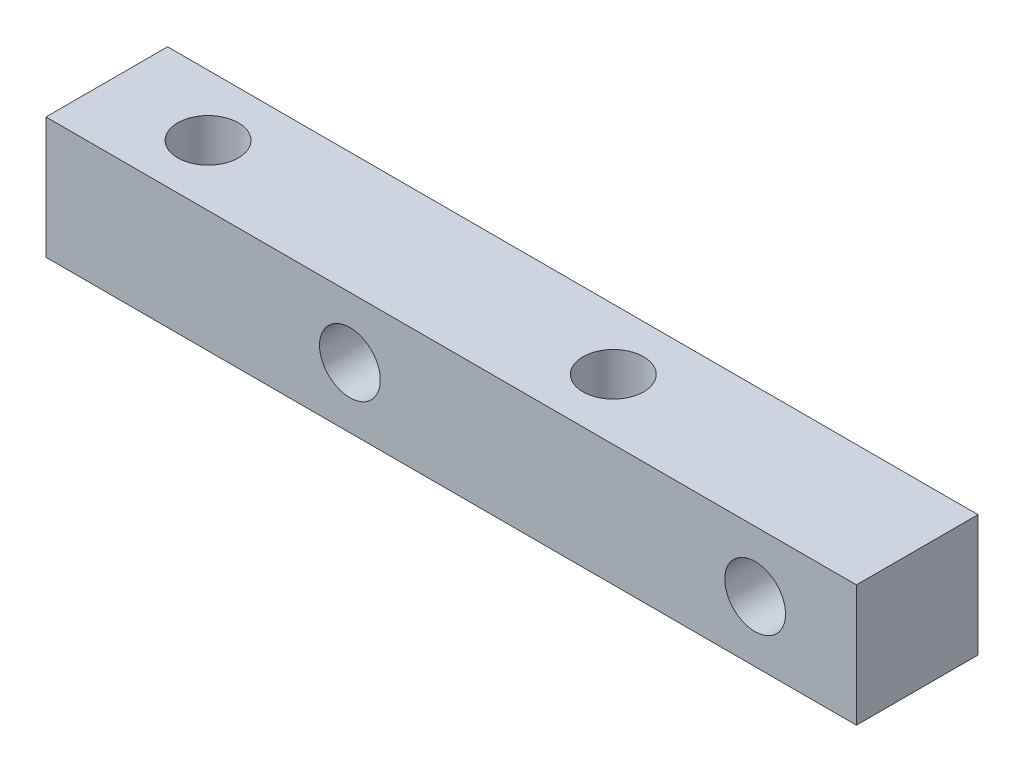
SolidWorks part; units mm, degrees
ref_plane "前视基准面" through (0, 0, 0) normal (0, 0, 1) x (1, 0, 0)
ref_plane "上视基准面" through (0, 0, 0) normal (0, 1, 0) x (1, 0, 0)
ref_plane "右视基准面" through (0, 0, 0) normal (1, 0, 0) x (0, 0, -1)
other "Configuration Table"
sketch "草图1" plane through (0, 0, 0) normal (0, 1, 0) x (1, 0, 0)
  line L1 (-20, 3) -> (20, 3)
  line L2 (-20, 3) -> (-20, -3)
  line L3 (-20, -3) -> (20, -3)
  line L4 (20, 3) -> (20, -3)
  line L5 (-20, 3) -> (20, -3) construction
  line L6 (-20, -3) -> (20, 3) construction
  point P0 (0, 0)
  dimension "D1" = 40
  dimension "D2" = 6
extrude "凸台-拉伸1" add sketch "草图1" along normal blind 6
sketch "草图2" plane through (0, 6, 0) normal (0, 1, 0) x (1, 0, 0)
  line L0 (-20, 0) -> (20, 0) construction
  line L1 (-20, 3) -> (-20, -3) construction
  line L2 (20, -3) -> (20, 3) construction
  circle A0 centre (-15, 0) radius 1.5
  circle A1 centre (5, 0) radius 1.5
  dimension "D1" = 3
  dimension "D2" = 5
  dimension "D3" = 20
extrude "切除-拉伸1" cut sketch "草图2" against normal through all
sketch "草图3" plane through (0, 0, -3) normal (0, 0, -1) x (-1, 0, 0)
  line L0 (-20, 3) -> (20, 3) construction
  line L1 (-20, 6) -> (-20, 0) construction
  line L2 (20, 6) -> (20, 0) construction
  circle A0 centre (-15, 3) radius 1.5
  circle A1 centre (5, 3) radius 1.5
  dimension "D1" = 3
  dimension "D2" = 5
  dimension "D3" = 20
extrude "切除-拉伸2" cut sketch "草图3" against normal through all
